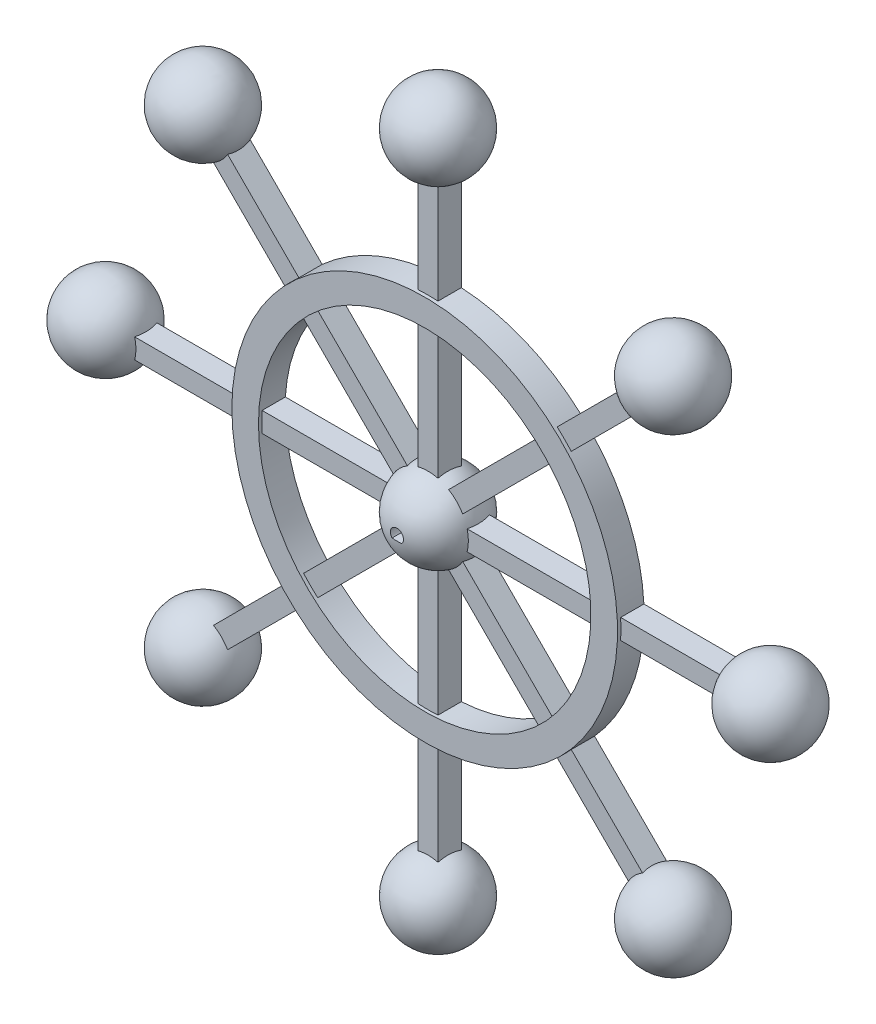
SolidWorks part; units mm, degrees
material "Plain Carbon Steel"
ref_plane "Front Plane" through (0, 0, 0) normal (0, 0, 1) x (1, 0, 0)
ref_plane "Top Plane" through (0, 0, 0) normal (0, 1, 0) x (1, 0, 0)
ref_plane "Right Plane" through (0, 0, 0) normal (1, 0, 0) x (0, 0, -1)
sketch "Sketch1" plane through (0, 0, 0) normal (0, 0, 1) x (1, 0, 0)
  line L0 (0, 15.875) -> (0, -15.875)
  arc A0 (0, -15.875) -> (0, 15.875) centre (0, 0) ccw
  dimension "D1" = 31.75
revolve "Revolve1" add sketch "Sketch1" angle 360 about L0
sketch "Sketch2" plane through (0, 0, 0) normal (0, 0, 1) x (1, 0, 0)
  line L0 (0, 0) -> (127, 0) construction
  line L1 (0, -3.81) -> (127, -3.81)
  line L2 (0, 3.81) -> (127, 3.81)
  line L3 (127, 3.81) -> (127, -3.81)
  line L4 (0, 3.81) -> (0, -3.81)
  dimension "D1" = 127
  dimension "D2" = 3.81
  dimension "D3" = 3.81
extrude "Boss-Extrude1" add sketch "Sketch2" along normal blind 3.81 and the other way blind 5.08
sketch "Sketch3" plane through (0, 0, 0) normal (0, 1, 0) x (1, 0, 0)
  line L0 (0, 0) -> (0, 8.1282) construction
pattern_circular "CirPattern1" count 8 over 360 about axis through (0, 0, 0) along (0, 0, 1) of "Boss-Extrude1"
sketch "Sketch5" plane through (0, 0, -5.08) normal (0, 0, -1) x (-1, 0, 0)
  circle A0 centre (0, 0) radius 63.5
  circle A1 centre (0, 0) radius 73.66
  dimension "D1" = 127
  dimension "D2" = 10.16
extrude "Boss-Extrude2" add sketch "Sketch5" against normal blind 10.16
sketch "Sketch6" plane through (0, 0, -5.08) normal (0, 0, -1) x (-1, 0, 0)
  line L0 (-1.8555, -1.6783) -> (1.8555, -1.6783)
  arc A0 (1.8555, -1.6783) -> (-1.8555, -1.6783) centre (0, 0) ccw
  dimension "D1" = 5.0038
  dimension "D2" = 3.711
extrude "Cut-Extrude1" cut sketch "Sketch6" against normal through all and the other way through all
sketch "Sketch7" plane through (0, 0, 0) normal (0, 0, 1) x (1, 0, 0)
  line L0 (3.81, 127) -> (-3.81, 127) construction
  line L1 (0, 111.125) -> (0, 142.875)
  arc A0 (0, 111.125) -> (0, 142.875) centre (0, 127) ccw
  dimension "D1" = 31.75
revolve "Revolve2" add sketch "Sketch7" angle 360 about L1
pattern_circular "CirPattern2" count 8 over 360 about axis through (0, 0, 0) along (0, 0, 1) of "Revolve2"
